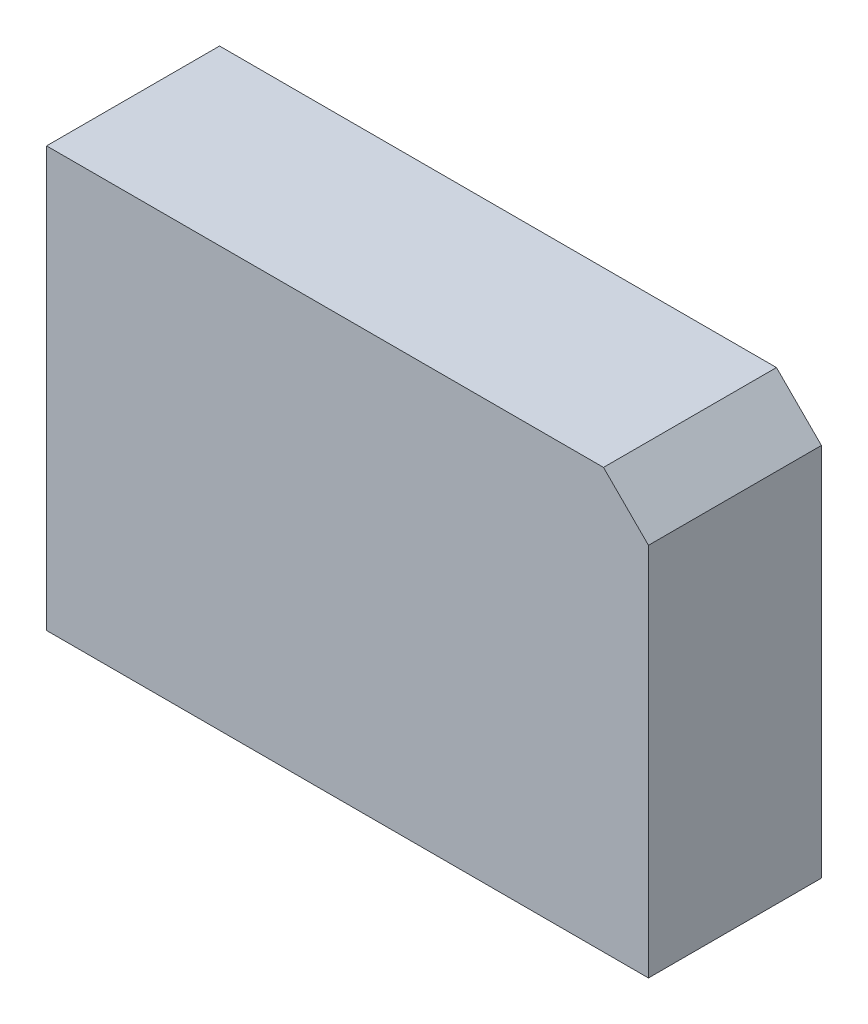
SolidWorks part; units mm, degrees
ref_plane "Front Plane" through (0, 0, 0) normal (0, 0, 1) x (1, 0, 0)
ref_plane "Top Plane" through (0, 0, 0) normal (0, 1, 0) x (1, 0, 0)
ref_plane "Right Plane" through (0, 0, 0) normal (1, 0, 0) x (0, 0, -1)
sketch "ChamferStockSketch" plane through (0, 0, 0) normal (0, 0, 1) x (1, 0, 0)
  line L1 (-21.375, -30.875) -> (43.875, -30.875)
  line L2 (-21.375, -30.875) -> (-21.375, 14.625)
  line L3 (-21.375, 14.625) -> (43.875, 14.625)
  line L4 (43.875, -30.875) -> (43.875, 14.625)
extrude "ChamferStockBoss" add sketch "ChamferStockSketch" along normal blind 18.75
chamfer "DistancePairEdgeChamfer" distance 4.875 1 edges at (43.875, 14.625, 9.375)
